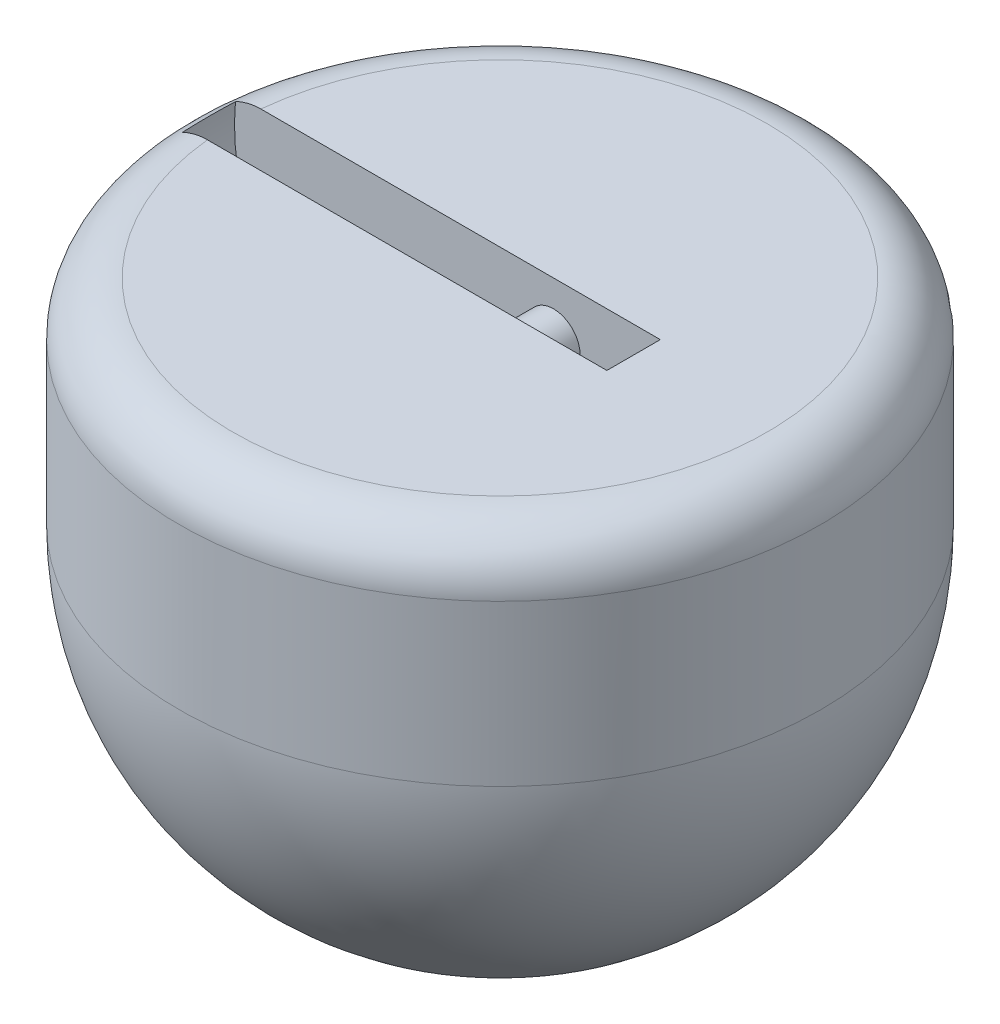
SolidWorks part; units mm, degrees
ref_plane "前视基准面" through (0, 0, 0) normal (0, 0, 1) x (1, 0, 0)
ref_plane "上视基准面" through (0, 0, 0) normal (0, 1, 0) x (1, 0, 0)
ref_plane "右视基准面" through (0, 0, 0) normal (1, 0, 0) x (0, 0, -1)
sketch "草图1" plane through (0, 0, 0) normal (0, 0, 1) x (1, 0, 0)
  line L0 (0, 0) -> (10, 0)
  line L1 (12, -2) -> (12, -8)
  line L2 (0, -20) -> (0, 0)
  arc A0 (10, 0) -> (12, -2) centre (10, -2) cw
  arc A1 (12, -8) -> (0, -20) centre (0, -8) cw
  dimension "D3" = 2
  dimension "D1" = 12
  dimension "D2" = 8
revolve "旋转1" add sketch "草图1" angle 360 about L2
sketch "草图2" plane through (0, 0, 0) normal (0, 0, 1) x (1, 0, 0)
  line L0 (10, 0) -> (-10, 0) construction
  line L1 (5, 0) -> (-10.8745, 0)
  arc A0 (5, 0) -> (-10.8745, 0) centre (-2.9373, -1) cw
  dimension "D1" = 8
  dimension "D2" = 1
  dimension "D3" = 5
extrude "切除-拉伸1" cut sketch "草图2" against normal mid plane 2
sketch "草图3" plane through (0, 0, 0) normal (0, 0, 1) x (1, 0, 0)
  line L0 (5, 0) -> (-9.9499, 0) construction
  circle A0 centre (1, -2) radius 1
  circle A1 centre (-3, -5) radius 1
  dimension "D1" = 2
  dimension "D2" = 2
  dimension "D3" = 4
  dimension "D4" = 3
  dimension "D5" = 1
extrude "凸台-拉伸1" add sketch "草图3" along normal mid plane 2
move or copy body "实体-移动/复制1" [suppressed] bodies to move or copy 108
